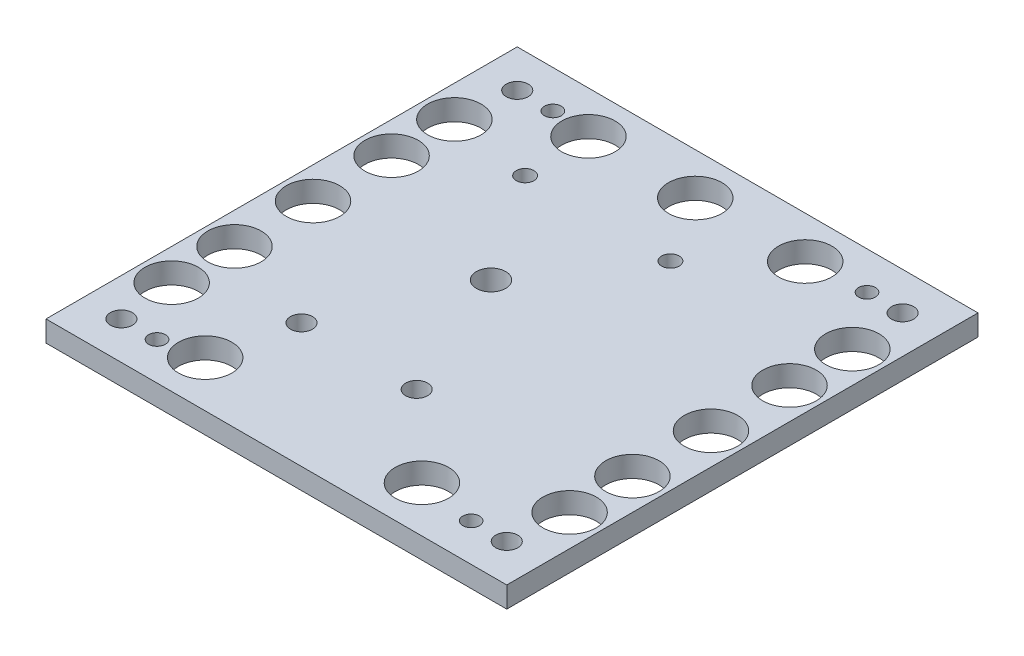
SolidWorks part; units mm, degrees
material "K110"
ref_plane "Front Plane" through (0, 0, 0) normal (0, 0, 1) x (1, 0, 0)
ref_plane "Top Plane" through (0, 0, 0) normal (0, 1, 0) x (1, 0, 0)
ref_plane "Right Plane" through (0, 0, 0) normal (1, 0, 0) x (0, 0, -1)
sketch "Sketch1" plane through (0, 0, 0) normal (0, 1, 0) x (1, 0, 0)
  line L1 (-110, -112.5) -> (110, -112.5)
  line L2 (-110, -112.5) -> (-110, 112.5)
  line L3 (-110, 112.5) -> (110, 112.5)
  line L4 (110, -112.5) -> (110, 112.5)
  line L5 (-110, -112.5) -> (110, 112.5) construction
  line L6 (-110, 112.5) -> (110, -112.5) construction
  point P0 (0, 0)
  dimension "D1" = 220
  dimension "D2" = 225
extrude "Boss-Extrude1" add sketch "Sketch1" along normal blind 10
sketch "Sketch3" plane through (0, 0, 0) normal (0, -1, 0) x (1, 0, 0)
  circle A0 centre (-19.87, -9.86) radius 7 construction
  circle A1 centre (-19.87, -9.86) radius 7
extrude "Cut-Extrude2" cut sketch "Sketch3" against normal up to next
hole_wizard "Ø8.0mm Dowel Hole1" positions "Sketch7" profile "Sketch5" hole size "Ø8.0" standard "ISO" end condition through all
sketch "Sketch7" plane through (0, 10, 0) normal (0, 1, 0) x (1, 0, 0)
  point P0 (75, -94.5)
  point P3 (-75, -94.5)
  point P6 (75, 94.5)
  point P10 (-75, 94.5)
sketch "Sketch5" plane through (75, 10, 94.5) normal (1, 0, 0) x (0, 0, 1)
  line L0 (0, 0) -> (0, 10)
  line L1 (0, 10) -> (4, 10)
  line L2 (4, 10) -> (4, 0)
  line L5 (4, 0) -> (0, 0)
  line L11 (0, -6.35) -> (0, 107.95) construction
  dimension "Thru Hole Dia." = 8
  dimension "Thru Hole Depth" = 10
hole_wizard "M10 Clearance Hole1" positions "Sketch10" profile "Sketch9" hole size "M10" standard "ISO" end condition through all
sketch "Sketch10" plane through (0, 10, 0) normal (0, 1, 0) x (1, 0, 0)
  point P0 (92, -94.5)
  point P3 (92, 94.5)
  point P6 (-92, 94.5)
  point P9 (-92, -94.5)
sketch "Sketch9" plane through (92, 10, 94.5) normal (1, 0, 0) x (0, 0, 1)
  line L0 (0, 0) -> (0, 10)
  line L1 (0, 10) -> (5.25, 10)
  line L2 (5.25, 10) -> (5.25, 0)
  line L5 (5.25, 0) -> (0, 0)
  line L11 (0, -6.35) -> (0, 107.95) construction
  dimension "Thru Hole Dia." = 10.5
  dimension "Thru Hole Depth" = 10
hole_wizard "M10 Clearance Hole2" positions "Sketch13" profile "Sketch12" hole size "M10" standard "ISO" end condition through all
sketch "Sketch13" plane through (0, 10, 0) normal (0, 1, 0) x (1, 0, 0)
  point P0 (7.63, -53.14)
  point P3 (-47.37, -53.14)
sketch "Sketch12" plane through (7.63, 10, 53.14) normal (1, 0, 0) x (0, 0, 1)
  line L0 (0, 0) -> (0, 10)
  line L1 (0, 10) -> (5.25, 10)
  line L2 (5.25, 10) -> (5.25, 0)
  line L5 (5.25, 0) -> (0, 0)
  line L11 (0, -6.35) -> (0, 107.95) construction
  dimension "Thru Hole Dia." = 10.5
  dimension "Thru Hole Depth" = 10
hole_wizard "M8 Clearance Hole1" positions "Sketch16" profile "Sketch15" hole size "M8" standard "ISO" end condition through all
sketch "Sketch16" plane through (0, 10, 0) normal (0, 1, 0) x (1, 0, 0)
  point P0 (15.13, 60.5)
  point P3 (-54.87, 61.13)
sketch "Sketch15" plane through (15.13, 10, -60.5) normal (1, 0, 0) x (0, 0, 1)
  line L0 (0, 0) -> (0, 10)
  line L1 (0, 10) -> (4.2, 10)
  line L2 (4.2, 10) -> (4.2, 0)
  line L5 (4.2, 0) -> (0, 0)
  line L11 (0, -6.35) -> (0, 107.95) construction
  dimension "Thru Hole Dia." = 8.4
  dimension "Thru Hole Depth" = 10
extrude "Cut-Extrude3" cut sketch "Sketch17" against normal up to next
sketch "Sketch17" plane through (89.63, 10, 0) normal (0, 1, 0) x (1, 0, 0)
  circle A15 centre (-184.63, 0) radius 12.75
  circle A16 centre (-184.63, -37.5) radius 12.75
  circle A17 centre (-184.63, -67.5) radius 12.75
  circle A18 centre (-145.63, -90.5) radius 12.75
  circle A19 centre (-42.13, -90.5) radius 12.75
  circle A20 centre (5.37, -67.5) radius 12.75
  circle A21 centre (5.37, -37.5) radius 12.75
  circle A22 centre (5.37, 0) radius 12.75
  circle A23 centre (-184.63, 37.5) radius 12.75
  circle A24 centre (-184.63, 67.5) radius 12.75
  circle A25 centre (5.37, 37.5) radius 12.75
  circle A26 centre (5.37, 67.5) radius 12.75
  circle A27 centre (-42.13, 92.5) radius 12.75
  circle A28 centre (-94.63, 92.5) radius 12.75
  circle A29 centre (-145.63, 92.5) radius 12.75
